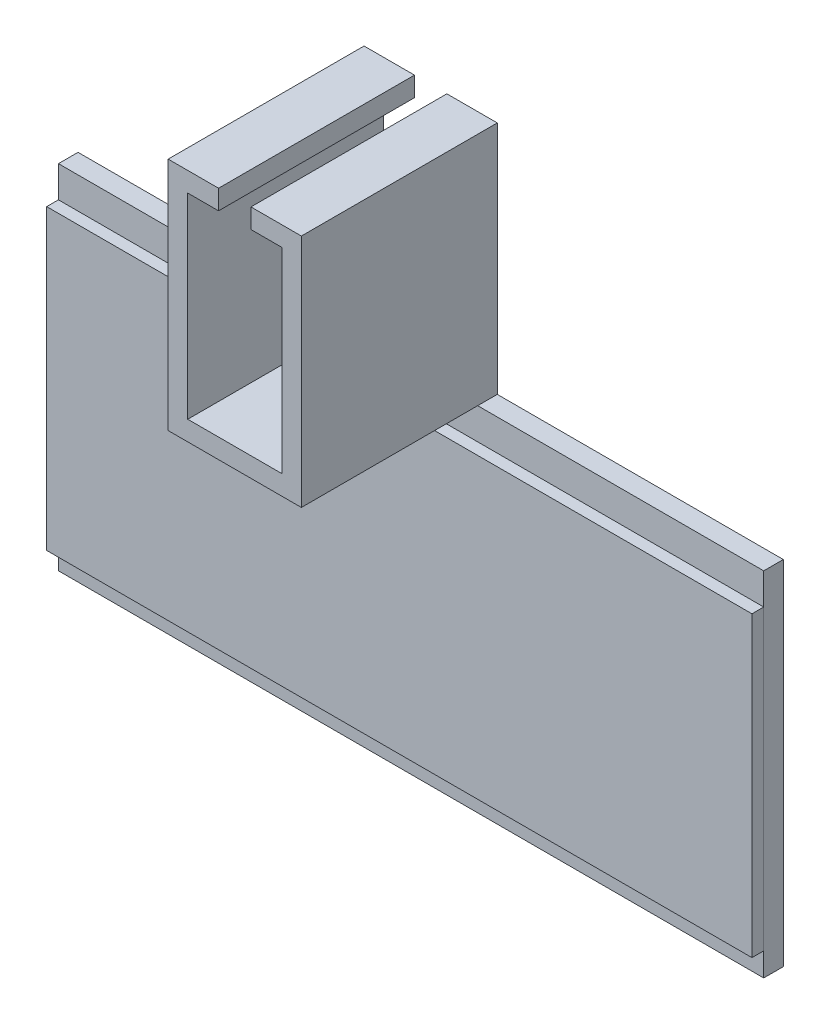
SolidWorks part; units mm, degrees
ref_plane "Ebene vorne" through (0, 0, 0) normal (0, 0, 1) x (1, 0, 0)
ref_plane "Ebene oben" through (0, 0, 0) normal (0, 1, 0) x (1, 0, 0)
ref_plane "Ebene rechts" through (0, 0, 0) normal (1, 0, 0) x (0, 0, -1)
sketch "Skizze1" plane through (0, 0, 0) normal (0, 0, 1) x (1, 0, 0)
  line L0 (-120, 0) -> (120, 0)
  line L1 (120, 0) -> (120, 500)
  line L2 (120, 500) -> (41.3483, 500)
  line L3 (41.3483, 500) -> (41.3483, 550)
  line L4 (41.3483, 550) -> (170, 550)
  line L5 (170, 550) -> (170, -50)
  line L6 (900, -50) -> (900, -950)
  line L7 (900, -950) -> (513.4831, -950)
  line L8 (170, -50) -> (900, -50)
  line L9 (0, -322.4719) -> (0, 738.2022) construction
  line L10 (513.4831, -950) -> (-513.4831, -950)
  line L11 (-170, -50) -> (-900, -50)
  line L12 (-900, -950) -> (-513.4831, -950)
  line L13 (-900, -50) -> (-900, -950)
  line L14 (-170, 550) -> (-170, -50)
  line L15 (-41.3483, 550) -> (-170, 550)
  line L16 (-41.3483, 500) -> (-41.3483, 550)
  line L17 (-120, 500) -> (-41.3483, 500)
  line L18 (-120, 0) -> (-120, 500)
  point P15 (0, -950)
  point P23 (0, 0)
  dimension "D1" = 500
  dimension "D2" = 120
  dimension "D3" = 50
  dimension "D4" = 50
  dimension "D5" = 50
  dimension "D6" = 900
  dimension "D7" = 900
extrude "Aufsatz-Linear austragen1" add sketch "Skizze1" along normal blind 500
sketch "Skizze2" plane through (900, 0, 0) normal (1, 0, 0) x (0, 0, -1)
  line L0 (-500, -50) -> (0, -50) construction
  line L1 (-500, -50) -> (-50, -50)
  line L2 (-500, -50) -> (-500, -950)
  line L3 (-500, -950) -> (-50, -950)
  line L4 (-50, -50) -> (-50, -950)
  line L5 (-500, -950) -> (-500, -50) construction
  line L6 (-500, -950) -> (0, -950) construction
  dimension "D1" = 450
extrude "Schnitt-Linear austragen1" cut sketch "Skizze2" against normal through all
sketch "Skizze3" plane through (900, 0, 0) normal (1, 0, 0) x (0, 0, -1)
  line L0 (-50, -950) -> (-50, -50) construction
  line L1 (-50, -130) -> (-80, -130)
  line L2 (-50, -130) -> (-50, -890)
  line L3 (-50, -890) -> (-80, -890)
  line L4 (-80, -130) -> (-80, -890)
  line L5 (-50, -950) -> (0, -950) construction
  dimension "D1" = 30
  dimension "D2" = 760
  dimension "D3" = 60
extrude "Aufsatz-Linear austragen2" add sketch "Skizze3" against normal blind 1800 separate body
